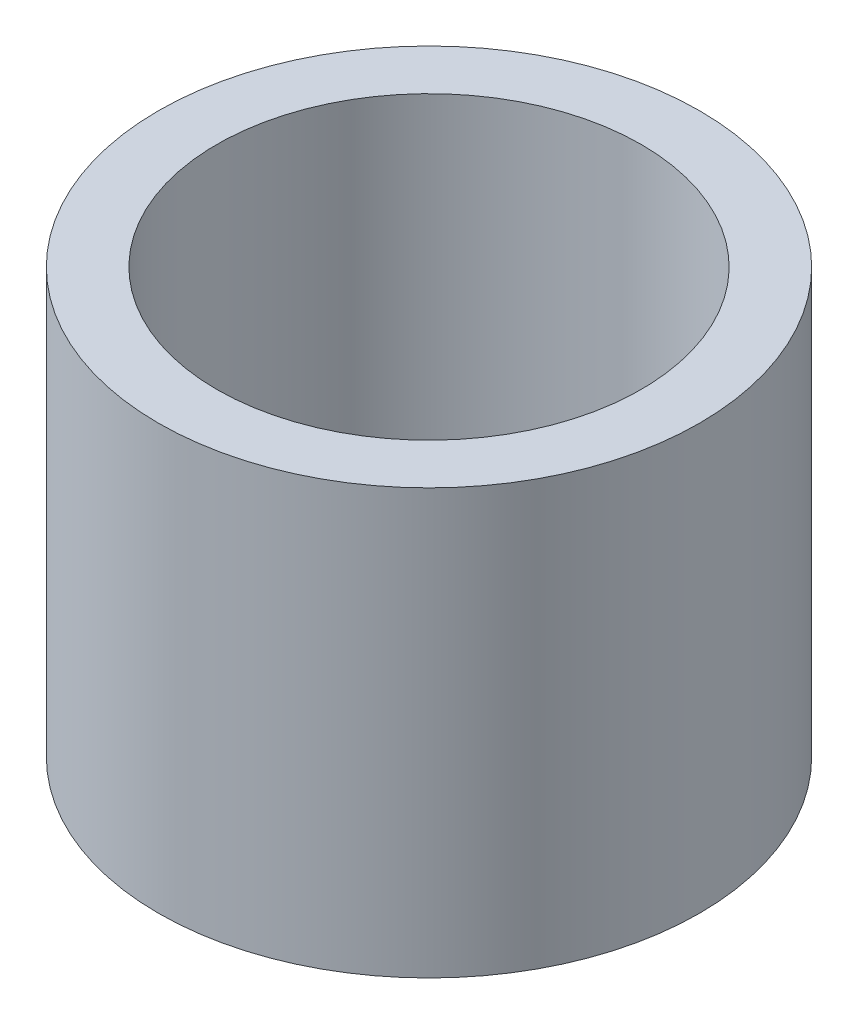
SolidWorks part; units mm, degrees
material "PTFE (general)"
ref_plane "Front Plane" through (0, 0, 0) normal (0, 0, 1) x (1, 0, 0)
ref_plane "Top Plane" through (0, 0, 0) normal (0, 1, 0) x (1, 0, 0)
ref_plane "Right Plane" through (0, 0, 0) normal (1, 0, 0) x (0, 0, -1)
sketch "Sketch2" plane through (0, 0, 0) normal (0, 1, 0) x (1, 0, 0)
  circle A0 centre (0, 0) radius 2
  circle A1 centre (0, 0) radius 2.55
  dimension "D1" = 4
  dimension "D2" = 5.1
extrude "Boss-Extrude1" add sketch "Sketch2" along normal blind 4
